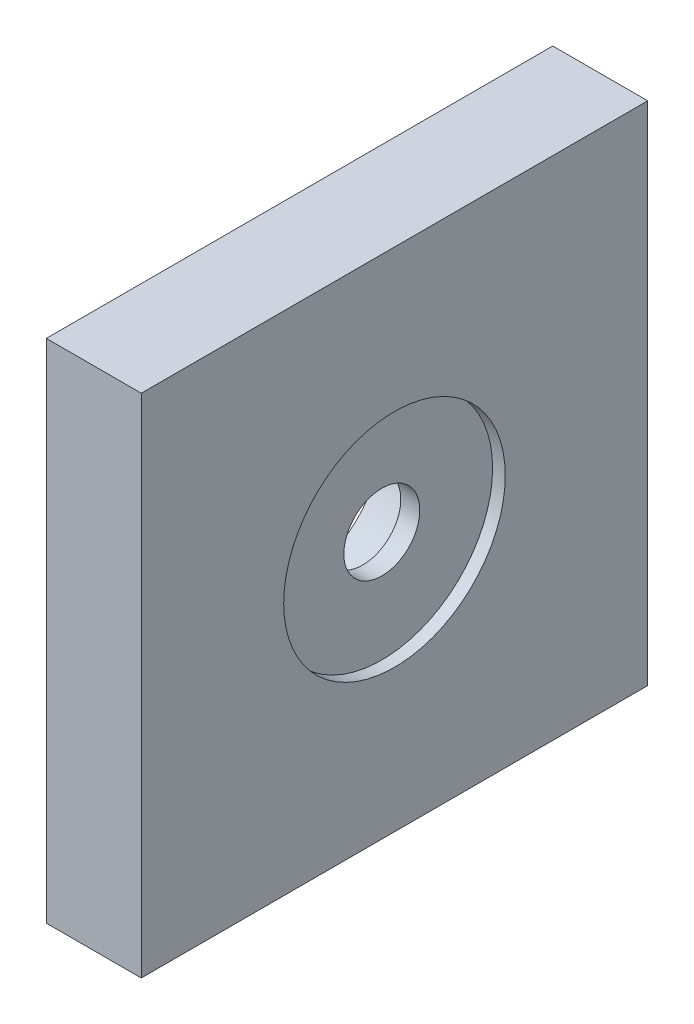
SolidWorks part; units mm, degrees
ref_plane "Спереди" through (0, 0, 0) normal (0, 0, 1) x (1, 0, 0)
ref_plane "Сверху" through (0, 0, 0) normal (0, 1, 0) x (1, 0, 0)
ref_plane "Справа" through (0, 0, 0) normal (1, 0, 0) x (0, 0, -1)
ref_plane "Плоскость1" through (0, 0, 0) normal (-1, 0, 0) x (0, -1, 0)
sketch "Эскиз1" plane through (0, 0, 0) normal (-1, 0, 0) x (0, -1, 0)
  line L0 (0, 0) -> (0, 80)
  line L1 (0, 80) -> (-80, 80)
  line L2 (-80, 80) -> (-80, 0)
  line L3 (-80, 0) -> (0, 0)
  point P4 (0, 0)
extrude "Бобышка-Вытянуть1" add sketch "Эскиз1" against normal blind 15
ref_plane "Плоскость2" through (0, 0, 40) normal (0, 0, -1) x (-1, 0, 0)
sketch "Эскиз2" plane through (0, 0, 40) normal (0, 0, -1) x (-1, 0, 0)
  line L0 (-15, 57.5) -> (-15, 40)
  line L1 (-15, 40) -> (0, 40)
  line L2 (0, 40) -> (0, 53)
  line L3 (0, 53) -> (-10, 53)
  line L4 (-10, 53) -> (-10, 46)
  line L5 (-10, 46) -> (-13, 46)
  line L6 (-13, 46) -> (-13, 57.5)
  line L7 (-13, 57.5) -> (-15, 57.5)
  line L8 (-15, 40) -> (0, 40) construction
revolve "Вырез-Повернуть1" cut sketch "Эскиз2" angle 360 about L8
